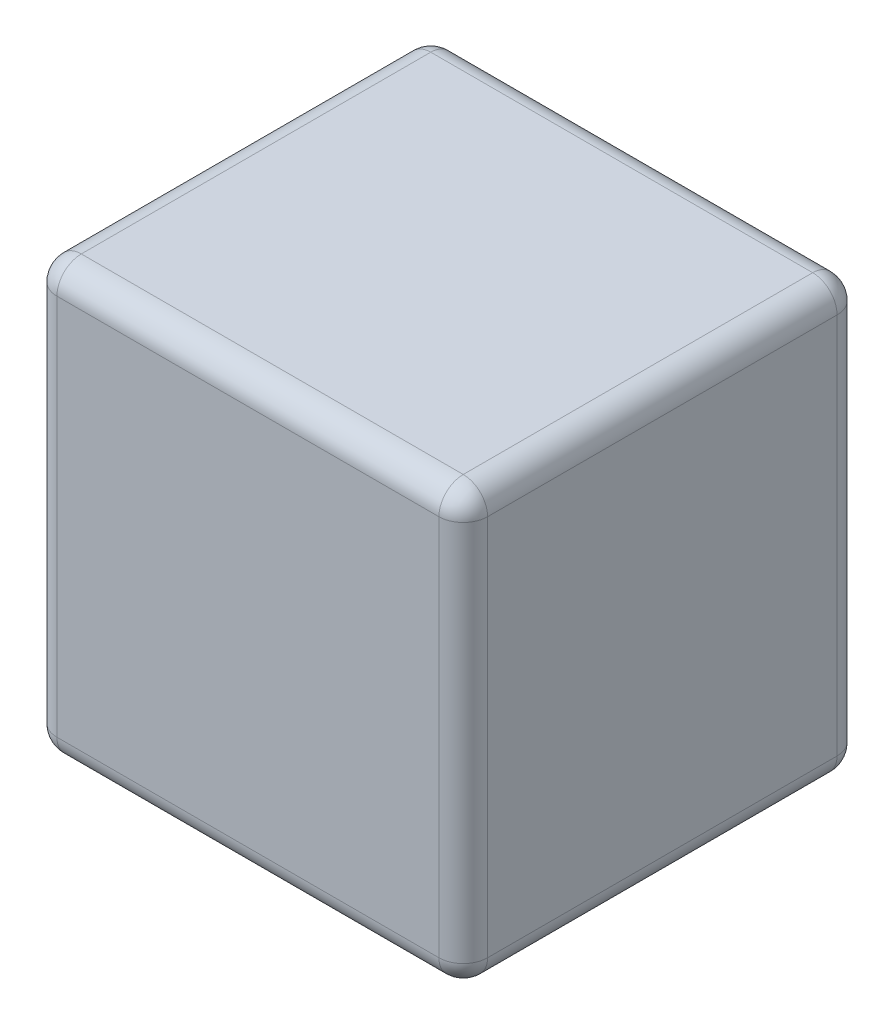
SolidWorks part; units mm, degrees
ref_plane "Alzado" through (0, 0, 0) normal (0, 0, 1) x (1, 0, 0)
ref_plane "Planta" through (0, 0, 0) normal (0, 1, 0) x (1, 0, 0)
ref_plane "Vista lateral" through (0, 0, 0) normal (1, 0, 0) x (0, 0, -1)
sketch "Croquis1" plane through (0, 0, 0) normal (0, 0, 1) x (1, 0, 0)
  line L1 (13.25, -13.25) -> (-13.25, -13.25)
  line L2 (13.25, -13.25) -> (13.25, 13.25)
  line L3 (13.25, 13.25) -> (-13.25, 13.25)
  line L4 (-13.25, -13.25) -> (-13.25, 13.25)
  line L5 (13.25, -13.25) -> (-13.25, 13.25) construction
  line L6 (13.25, 13.25) -> (-13.25, -13.25) construction
  point P0 (0, 0)
  dimension "D1" = 26.5
extrude "Saliente-Extruir1" add sketch "Croquis1" along normal blind 24.5
fillet "Redondeo1" radius 1.5 12 edges at (-13.25, 13.25, 12.25) (-13.25, 0, 24.5) (-13.25, -13.25, 12.25) (0, -13.25, 0) (0, 13.25, 0) (-13.25, 0, 0) (13.25, -13.25, 12.25) (13.25, 0, 24.5) (13.25, 13.25, 12.25) (13.25, 0, 0) (0, -13.25, 24.5) (0, 13.25, 24.5)
